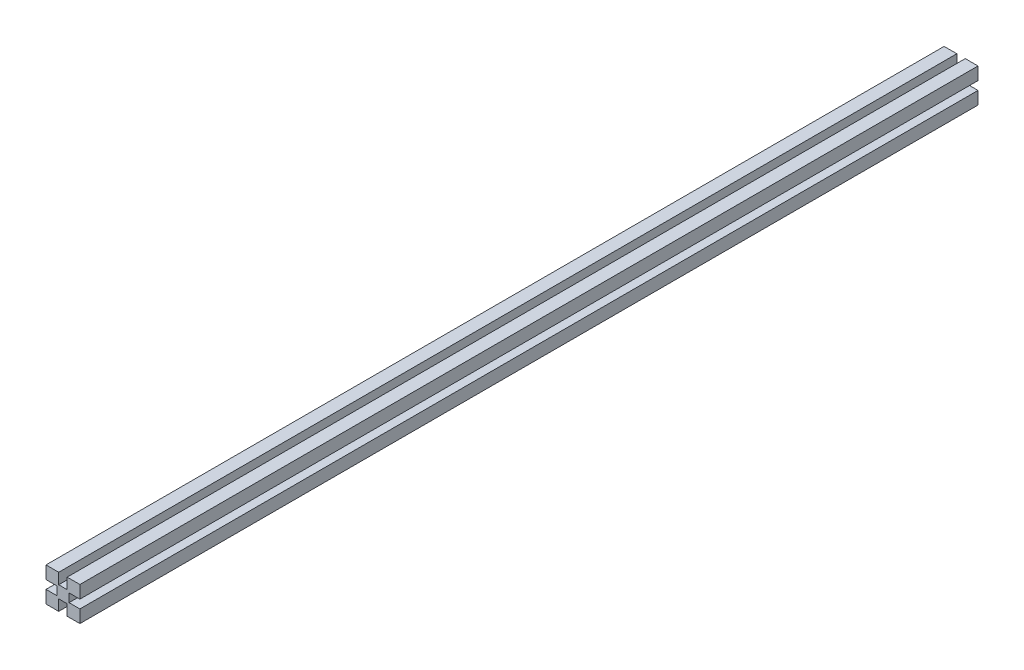
SolidWorks part; units mm, degrees
ref_plane "Front Plane" through (0, 0, 0) normal (0, 0, 1) x (1, 0, 0)
ref_plane "Top Plane" through (0, 0, 0) normal (0, 1, 0) x (1, 0, 0)
ref_plane "Right Plane" through (0, 0, 0) normal (1, 0, 0) x (0, 0, -1)
sketch "Sketch1" plane through (0, 0, 0) normal (0, 0, 1) x (1, 0, 0)
  line L0 (-12.7, 12.7) -> (-12.7, 3.175)
  line L5 (-12.7, 3.175) -> (-4.572, 3.175)
  line L6 (-4.572, 3.175) -> (-4.572, -3.175)
  line L7 (-4.572, -3.175) -> (-12.7, -3.175)
  line L8 (-12.7, -3.175) -> (-12.7, -12.7)
  line L9 (-12.7, -12.7) -> (-3.175, -12.7)
  line L10 (-3.175, -12.7) -> (-3.175, -4.572)
  line L11 (-3.175, -4.572) -> (3.175, -4.572)
  line L12 (3.175, -4.572) -> (3.175, -12.7)
  line L13 (3.175, -12.7) -> (12.7, -12.7)
  line L14 (12.7, -12.7) -> (12.7, -3.175)
  line L15 (12.7, -3.175) -> (4.572, -3.175)
  line L16 (4.572, -3.175) -> (4.572, 3.175)
  line L17 (4.572, 3.175) -> (12.7, 3.175)
  line L18 (12.7, 3.175) -> (12.7, 12.7)
  line L20 (-12.7, 12.7) -> (-3.175, 12.7)
  line L21 (-3.175, 12.7) -> (-3.175, 4.572)
  line L22 (-3.175, 4.572) -> (3.175, 4.572)
  line L23 (3.175, 4.572) -> (3.175, 12.7)
  line L24 (3.175, 12.7) -> (12.7, 12.7)
  point P0 (0, 0)
  point P19 (4.572, 0)
  point P23 (0, -4.572)
  dimension "D1" = 25.4
  dimension "D2" = 25.4
  dimension "D3" = 9.144
  dimension "D4" = 9.144
  dimension "D5" = 6.35
  dimension "D6" = 6.35
  dimension "D7" = 9.525
  dimension "D8" = 9.525
  dimension "D9" = 8.128
  dimension "D10" = 8.128
extrude "Boss-Extrude1" add sketch "Sketch1" along normal blind 673.1
